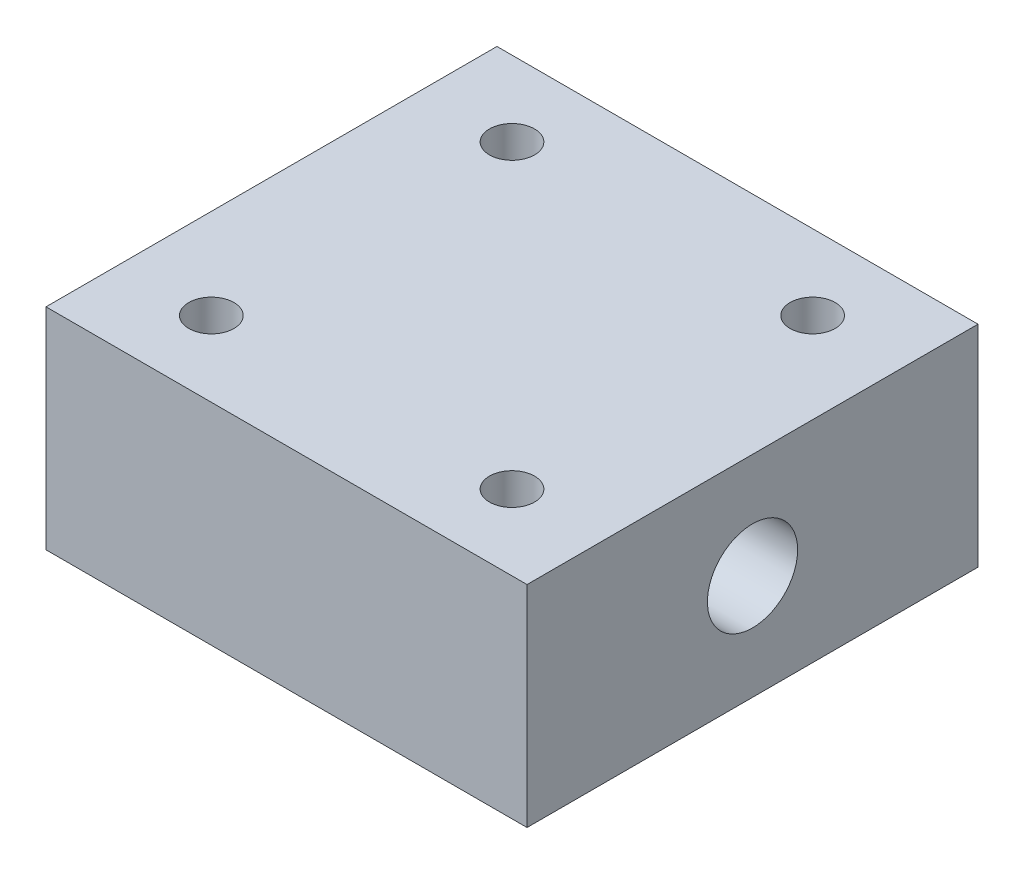
SolidWorks part; units mm, degrees
material "普通碳钢"
ref_plane "前视基准面" through (0, 0, 0) normal (0, 0, 1) x (1, 0, 0)
ref_plane "上视基准面" through (0, 0, 0) normal (0, 1, 0) x (1, 0, 0)
ref_plane "右视基准面" through (0, 0, 0) normal (1, 0, 0) x (0, 0, -1)
sketch "草图1" plane through (0, 0, 0) normal (0, 0, 1) x (1, 0, 0)
  line L1 (-16, -7) -> (16, -7)
  line L2 (-16, -7) -> (-16, 7)
  line L3 (-16, 7) -> (16, 7)
  line L4 (16, -7) -> (16, 7)
  line L5 (-16, -7) -> (16, 7) construction
  line L6 (-16, 7) -> (16, -7) construction
  point P0 (0, 0)
  dimension "D1" = 32
  dimension "D2" = 14
extrude "凸台-拉伸1" add sketch "草图1" against normal blind 30
sketch "草图2" plane through (0, 7, 0) normal (0, 1, 0) x (1, 0, 0)
  line L0 (0, 30) -> (0, 0) construction
  line L1 (16, 30) -> (-16, 30) construction
  line L2 (16, 0) -> (-16, 0) construction
  line L3 (-16, 15) -> (16, 15) construction
  line L4 (-16, 30) -> (-16, 0) construction
  line L5 (16, 30) -> (16, 0) construction
  circle A0 centre (-10, 25) radius 1.5
  circle A1 centre (10, 25) radius 1.5
  circle A2 centre (10, 5) radius 1.5
  circle A3 centre (-10, 5) radius 1.5
  point P14 (0, 0)
  point P16 (-9.7935, 15)
  point P17 (-8.4408, 22.7239)
  dimension "D1" = 3
  dimension "D2" = 10
  dimension "D3" = 10
extrude "切除-拉伸1" cut sketch "草图2" against normal blind 10
sketch "草图3" plane through (16, 0, 0) normal (1, 0, 0) x (0, 0, -1)
  line L0 (15, 7) -> (15, -7) construction
  line L1 (30, 7) -> (0, 7) construction
  line L2 (30, -7) -> (0, -7) construction
  circle A0 centre (15, 0) radius 3
  dimension "D1" = 6
extrude "切除-拉伸2" cut sketch "草图3" against normal up to next
